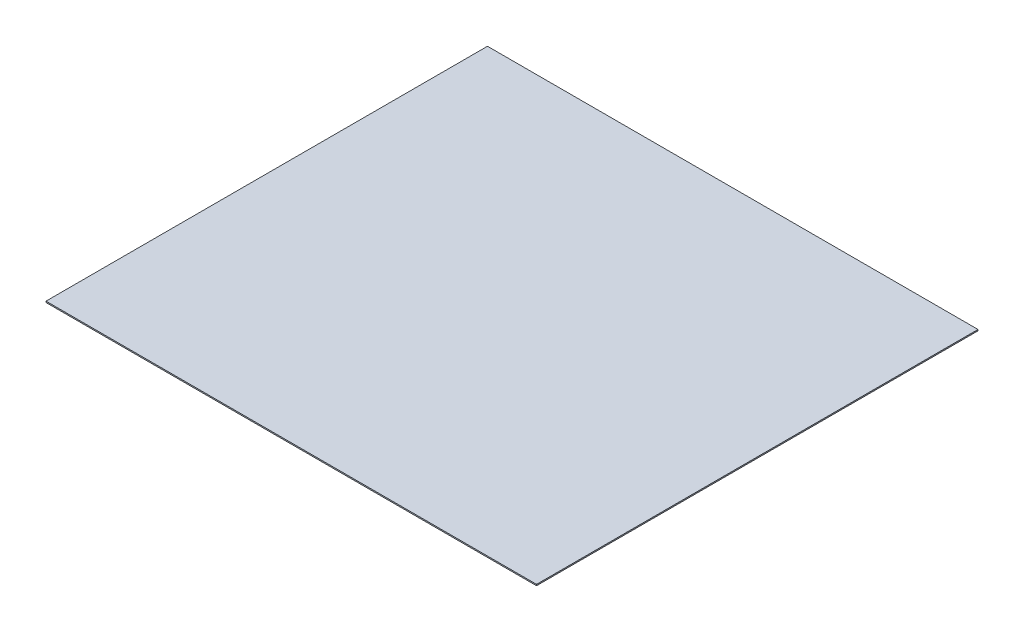
SolidWorks part; units mm, degrees
ref_plane "Front Plane" through (0, 0, 0) normal (0, 0, 1) x (1, 0, 0)
ref_plane "Top Plane" through (0, 0, 0) normal (0, 1, 0) x (1, 0, 0)
ref_plane "Right Plane" through (0, 0, 0) normal (1, 0, 0) x (0, 0, -1)
sketch "Sketch1" plane through (0, 0, 0) normal (0, 1, 0) x (1, 0, 0)
  line L0 (0, 160) -> (0, 0) construction
  line L1 (-220, 180) -> (180, 180)
  line L2 (-220, 180) -> (-220, -180)
  line L3 (-220, -180) -> (180, -180)
  line L4 (180, 180) -> (180, -180)
  line L5 (-160, 160) -> (160, 160) construction
  line L6 (-160, 160) -> (-160, -160) construction
  line L7 (-160, -160) -> (160, -160) construction
  line L8 (160, 160) -> (160, -160) construction
  line L9 (0, 0) -> (160, 0) construction
  line L10 (0, 0) -> (-160, 0) construction
  line L11 (0, 0) -> (0, -160) construction
  line L12 (-120, 160) -> (-120, -160) construction
  line L13 (-80, 160) -> (-80, -160) construction
  line L14 (-40, 160) -> (-40, -160) construction
  line L15 (0, 160) -> (0, -160) construction
  line L16 (40, 160) -> (40, -160) construction
  line L17 (80, 160) -> (80, -160) construction
  line L18 (120, 160) -> (120, -160) construction
  line L19 (-160, 120) -> (160, 120) construction
  line L20 (-160, 80) -> (160, 80) construction
  line L21 (-160, 40) -> (160, 40) construction
  line L22 (-160, 0) -> (160, 0) construction
  line L23 (-160, -40) -> (160, -40) construction
  line L24 (-160, -80) -> (160, -80) construction
  line L25 (-160, -120) -> (160, -120) construction
  dimension "D1" = 360
  dimension "D2" = 400
  dimension "D3" = 320
  dimension "D4" = 320
  dimension "D5" = 20
  dimension "D6" = 20
extrude "Boss-Extrude1" add sketch "Sketch1" along normal blind 1
